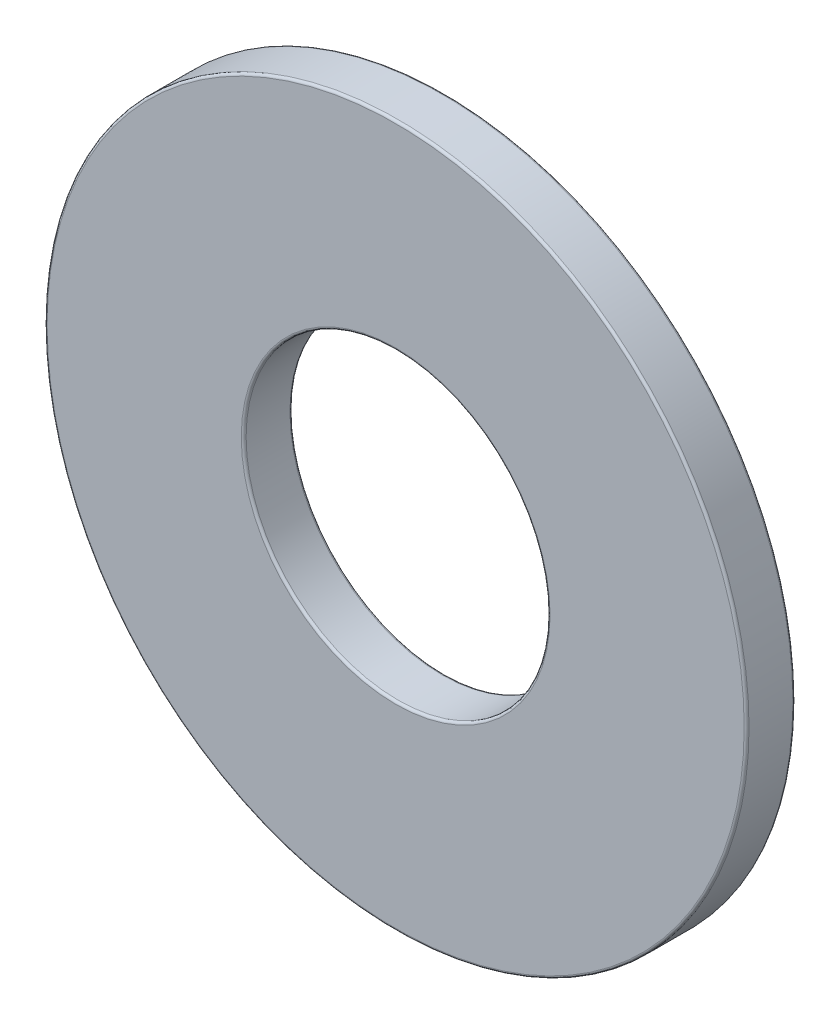
SolidWorks part; units mm, degrees
ref_plane "Front Plane" through (0, 0, 0) normal (0, 0, 1) x (1, 0, 0)
ref_plane "Top Plane" through (0, 0, 0) normal (0, 1, 0) x (1, 0, 0)
ref_plane "Right Plane" through (0, 0, 0) normal (1, 0, 0) x (0, 0, -1)
sketch "Sketch1" plane through (0, 0, 0) normal (0, 0, 1) x (1, 0, 0)
  circle A0 centre (0, 0) radius 23.8125
  circle A1 centre (0, 0) radius 10.3124
  dimension "OD" = 47.625
  dimension "ID" = 20.6248
sketch "Sketch2" plane through (0, 0, 0) normal (1, 0, 0) x (0, 0, -1)
  line L0 (-1.651, 0) -> (1.651, 0) construction
sketch "Sketch3" plane through (0, 0, 0) normal (0, 0, 1) x (1, 0, 0)
  circle A0 centre (0, 0) radius 10.3124 construction
  circle A1 centre (0, 0) radius 23.8125 construction
  circle A2 centre (0, 0) radius 10.3124
  circle A3 centre (0, 0) radius 23.8125
extrude "Boss-Extrude1" add sketch "Sketch3" along normal mid plane 3.302
fillet "Fillet1" radius 0.1651 4 edges at (10.3124, 0, -1.651) (23.8125, 0, -1.651) (10.3124, 0, 1.651) (23.8125, 0, 1.651)
equation "\"D1@Boss-Extrude1\"=\"thickness max@sketch2\""
equation "\"D1@Fillet1\"=\"thickness max@sketch2\"*0.05"
